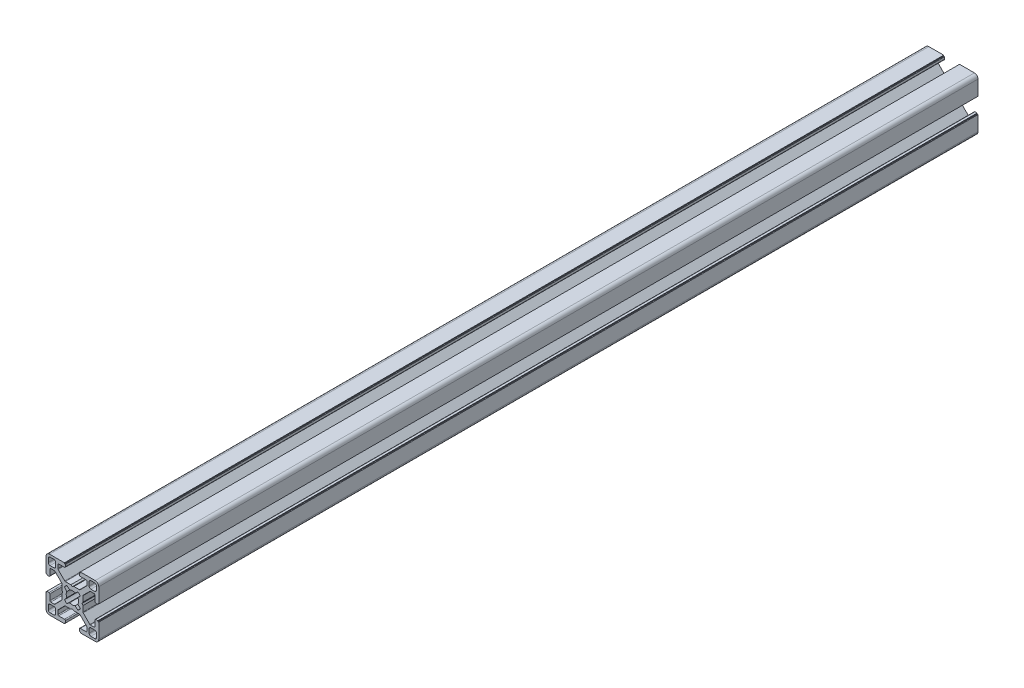
SolidWorks part; units mm, degrees
ref_plane "Front Plane" through (0, 0, 0) normal (0, 0, 1) x (1, 0, 0)
ref_plane "Top Plane" through (0, 0, 0) normal (0, 1, 0) x (1, 0, 0)
ref_plane "Right Plane" through (0, 0, 0) normal (1, 0, 0) x (0, 0, -1)
sketch "Sketch1" plane through (0, 0, 0) normal (0, 0, 1) x (1, 0, 0)
  line L0 (-15, 0) -> (15, 0) construction
  line L1 (0, -15) -> (0, 15) construction
  line L2 (-4.5, 15) -> (4.5, 15) construction
  line L3 (-4, -15) -> (4, -15) construction
  line L4 (-4.5, 15) -> (-4.5, 14.5)
  line L5 (-4.5, 14.5) -> (-4, 14.5)
  line L6 (-4, 14.5) -> (-4, 13.29)
  line L7 (-4.5, 12.79) -> (-7.7675, 12.79)
  line L8 (-8.2675, 12.29) -> (-8.2675, 10.2707)
  line L9 (-8.1211, 9.9171) -> (-4.3504, 6.1464)
  line L10 (-3.9968, 6) -> (0, 6)
  line L11 (0, 0) -> (-15, 15) construction
  line L12 (-4.5, 15) -> (-12.968, 15)
  line L14 (-12.705, 9.5135) -> (-10.5135, 9.5135)
  line L15 (-13.705, 10.5135) -> (-13.705, 12.705)
  line L16 (-12.705, 13.705) -> (-10.5135, 13.705)
  line L17 (-9.5135, 10.5135) -> (-9.5135, 12.705)
  line L18 (-13.705, 9.5135) -> (-9.5135, 13.705) construction
  line L19 (-13.705, 13.705) -> (-9.5135, 9.5135) construction
  line L20 (-3.1568, 4.5038) -> (-1.5303, 3.1477) construction
  line L21 (-4.5038, 3.1568) -> (-3.1477, 1.5303) construction
  line L22 (-6, 3.9968) -> (-6, 0)
  line L23 (-9.9171, 8.1211) -> (-6.1464, 4.3504)
  line L24 (-15, 4.5) -> (-15, 12.968)
  line L25 (-12.29, 8.2675) -> (-10.2707, 8.2675)
  line L26 (-12.79, 4.5) -> (-12.79, 7.7675)
  line L27 (-14.5, 4) -> (-13.29, 4)
  line L28 (-14.5, 4.5) -> (-14.5, 4)
  line L29 (-15, 4.5) -> (-14.5, 4.5)
  circle A0 centre (0, 0) radius 3.5
  arc A1 (-12.968, 15) -> (-15, 12.968) centre (-12.968, 12.968) ccw
  circle A2 centre (0, 0) radius 5.5 construction
  arc A3 (-10.5135, 9.5135) -> (-9.5135, 10.5135) centre (-10.5135, 10.5135) ccw
  arc A4 (-13.705, 12.705) -> (-12.705, 13.705) centre (-12.705, 12.705) cw
  arc A5 (-10.5135, 13.705) -> (-9.5135, 12.705) centre (-10.5135, 12.705) cw
  arc A6 (-12.705, 9.5135) -> (-13.705, 10.5135) centre (-12.705, 10.5135) cw
  arc A7 (-12.79, 4.5) -> (-13.29, 4) centre (-13.29, 4.5) cw
  arc A8 (-12.29, 8.2675) -> (-12.79, 7.7675) centre (-12.29, 7.7675) ccw
  arc A9 (-9.9171, 8.1211) -> (-10.2707, 8.2675) centre (-10.2707, 7.7675) ccw
  arc A10 (-6, 3.9968) -> (-6.1464, 4.3504) centre (-6.5, 3.9968) ccw
  arc A11 (-4.3504, 6.1464) -> (-3.9968, 6) centre (-3.9968, 6.5) ccw
  arc A12 (-4, 13.29) -> (-4.5, 12.79) centre (-4.5, 13.29) cw
  arc A13 (-7.7675, 12.79) -> (-8.2675, 12.29) centre (-7.7675, 12.29) ccw
  arc A14 (-8.2675, 10.2707) -> (-8.1211, 9.9171) centre (-7.7675, 10.2707) ccw
  point P4 (0, 0)
  point P8 (0, 0)
  point P13 (0, 15)
  point P15 (0, -15)
  point P16 (0, 6)
  point P23 (-11.6092, 11.6093)
  point P26 (0, 6)
  point P62 (-12.79, 4)
  point P65 (-12.79, 8.2675)
  point P68 (-10.0636, 8.2675)
  point P71 (-6, 4.2039)
  point P74 (-4.2039, 6)
  point P77 (-4, 12.79)
  point P80 (-8.2675, 12.79)
  point P83 (-8.2675, 10.0636)
  dimension "Center Hole Diameter" = 7
  dimension "D11" = 2.032
  dimension "D9" = 11
  dimension "D13" = 1
  dimension "D14" = 0.5
  dimension "Rail Height" = 30
  dimension "Rail Width" = 30
  dimension "T-Slot Width" = 8
  dimension "T-Slot Depth" = 9
  dimension "D1" = 9
  dimension "D2" = 45
  dimension "D3" = 8
  dimension "D4" = 2.21
  dimension "D5" = 16.535
  dimension "D7" = 2.54
  dimension "D6" = 1.295
  dimension "D8" = 1.246
  dimension "D10" = 10.36
  dimension "D12" = 1.905
sketch "Sketch2" plane through (0, 0, 0) normal (1, 0, 0) x (0, 0, -1)
  line L0 (-76.2, 0) -> (76.2, 0) construction
  line L2 (0, -15) -> (0, 15) construction
  line L3 (0, -15) -> (0, 15) construction
  line L4 (-76.2, -15) -> (-76.2, 15) construction
  line L5 (76.2, -15) -> (76.2, 15) construction
  point P0 (-38.7, 0)
  point P3 (0, 0)
  point P4 (38.7, 0)
  point P12 (-76.2, 0)
  point P14 (76.2, 0)
  dimension "Length" = 152.4
  dimension "D1" = 37.5
sketch "Sketch3" plane through (0, 0, 0) normal (0, 0, 1) x (1, 0, 0)
  line L0 (-4.5038, 3.1568) -> (-3.1477, 1.5303)
  line L1 (0, 3.5) -> (0, 5.5)
  line L2 (-5.5, 0) -> (-3.5, 0)
  line L7 (-6, 3.9968) -> (-6, 0) construction
  line L31 (-9.9171, 8.1211) -> (-6.1464, 4.3504) construction
  line L117 (-12.29, 8.2675) -> (-10.2707, 8.2675) construction
  line L118 (-12.79, 4.5) -> (-12.79, 7.7675) construction
  line L157 (-12.705, 9.5135) -> (-10.5135, 9.5135)
  line L158 (-9.5135, 10.5135) -> (-9.5135, 12.705)
  line L163 (-10.5135, 13.705) -> (-12.705, 13.705)
  line L164 (-13.705, 12.705) -> (-13.705, 10.5135)
  line L165 (-12.705, 9.5135) -> (-10.5135, 9.5135)
  line L166 (-9.5135, 10.5135) -> (-9.5135, 12.705)
  line L167 (-10.5135, 13.705) -> (-12.705, 13.705)
  line L168 (-13.705, 12.705) -> (-13.705, 10.5135)
  line L169 (-14.5, 4) -> (-13.29, 4) construction
  line L170 (-14.5, 4.5) -> (-14.5, 4) construction
  line L171 (-15, 4.5) -> (-14.5, 4.5) construction
  line L172 (-15, 4.5) -> (-15, 12.968) construction
  line L173 (-4.5, 15) -> (-12.968, 15) construction
  line L174 (-4.5, 15) -> (-4.5, 14.5) construction
  line L175 (-4.5, 14.5) -> (-4, 14.5) construction
  line L176 (-4, 14.5) -> (-4, 13.29) construction
  line L177 (-4.5, 12.79) -> (-7.7675, 12.79) construction
  line L178 (-8.2675, 12.29) -> (-8.2675, 10.2707) construction
  line L179 (-8.1211, 9.9171) -> (-4.3504, 6.1464) construction
  line L180 (-3.9968, 6) -> (0, 6) construction
  line L181 (-6, 3.9968) -> (-6, 0.866)
  line L182 (-9.9171, 8.1211) -> (-6.1464, 4.3504)
  line L183 (-12.29, 8.2675) -> (-10.2707, 8.2675)
  line L184 (-12.79, 4.5) -> (-12.79, 7.7675)
  line L185 (-14.5, 4) -> (-13.29, 4)
  line L186 (-14.5, 4.5) -> (-14.5, 4)
  line L187 (-15, 4.5) -> (-14.5, 4.5)
  line L188 (-15, 4.5) -> (-15, 12.968)
  line L189 (-4.5, 15) -> (-12.968, 15)
  line L190 (-4.5, 15) -> (-4.5, 14.5)
  line L191 (-4.5, 14.5) -> (-4, 14.5)
  line L192 (-4, 14.5) -> (-4, 13.29)
  line L193 (-4.5, 12.79) -> (-7.7675, 12.79)
  line L194 (-8.2675, 12.29) -> (-8.2675, 10.2707)
  line L195 (-8.1211, 9.9171) -> (-4.3504, 6.1464)
  line L196 (-3.9968, 6) -> (-0.866, 6)
  line L197 (-0.866, 6) -> (0, 5.5)
  line L198 (0, -15) -> (0, 15) construction
  line L199 (0, 0) -> (-15, 15) construction
  line L200 (0, 0) -> (-15, 15) construction
  line L201 (-3.1568, 4.5038) -> (-1.5303, 3.1477) construction
  line L202 (-3.1568, 4.5038) -> (-1.5303, 3.1477)
  line L203 (-6, 0.866) -> (-5.5, 0)
  line L204 (-15, 0) -> (15, 0) construction
  line L205 (-15, 0) -> (15, 0) construction
  line L206 (0, -15) -> (0, 15) construction
  arc A0 (-3.5, 0) -> (-3.1477, 1.5303) centre (0, 0) cw
  arc A10 (-6, 3.9968) -> (-6.1464, 4.3504) centre (-6.5, 3.9968) ccw construction
  circle A16 centre (0, 0) radius 3.5
  arc A18 (0, 3.5) -> (-1.5303, 3.1477) centre (0, 0) ccw
  arc A20 (-9.9171, 8.1211) -> (-10.2707, 8.2675) centre (-10.2707, 7.7675) ccw construction
  arc A22 (-12.29, 8.2675) -> (-12.79, 7.7675) centre (-12.29, 7.7675) ccw construction
  arc A28 (-13.29, 4) -> (-12.79, 4.5) centre (-13.29, 4.5) ccw construction
  arc A29 (-10.5135, 9.5135) -> (-9.5135, 10.5135) centre (-10.5135, 10.5135) ccw
  arc A30 (-9.5135, 12.705) -> (-10.5135, 13.705) centre (-10.5135, 12.705) ccw
  arc A31 (-12.705, 13.705) -> (-13.705, 12.705) centre (-12.705, 12.705) ccw
  arc A32 (-13.705, 10.5135) -> (-12.705, 9.5135) centre (-12.705, 10.5135) ccw
  arc A33 (-10.5135, 9.5135) -> (-9.5135, 10.5135) centre (-10.5135, 10.5135) ccw
  arc A34 (-9.5135, 12.705) -> (-10.5135, 13.705) centre (-10.5135, 12.705) ccw
  arc A35 (-12.705, 13.705) -> (-13.705, 12.705) centre (-12.705, 12.705) ccw
  arc A36 (-13.705, 10.5135) -> (-12.705, 9.5135) centre (-12.705, 10.5135) ccw
  arc A37 (-12.968, 15) -> (-15, 12.968) centre (-12.968, 12.968) ccw construction
  arc A38 (-4.5, 12.79) -> (-4, 13.29) centre (-4.5, 13.29) ccw construction
  arc A39 (-7.7675, 12.79) -> (-8.2675, 12.29) centre (-7.7675, 12.29) ccw construction
  arc A40 (-8.2675, 10.2707) -> (-8.1211, 9.9171) centre (-7.7675, 10.2707) ccw construction
  arc A41 (-4.3504, 6.1464) -> (-3.9968, 6) centre (-3.9968, 6.5) ccw construction
  arc A42 (-6, 3.9968) -> (-6.1464, 4.3504) centre (-6.5, 3.9968) ccw
  arc A43 (-9.9171, 8.1211) -> (-10.2707, 8.2675) centre (-10.2707, 7.7675) ccw
  arc A44 (-12.29, 8.2675) -> (-12.79, 7.7675) centre (-12.29, 7.7675) ccw
  arc A45 (-13.29, 4) -> (-12.79, 4.5) centre (-13.29, 4.5) ccw
  arc A46 (-12.968, 15) -> (-15, 12.968) centre (-12.968, 12.968) ccw
  arc A47 (-4.5, 12.79) -> (-4, 13.29) centre (-4.5, 13.29) ccw
  arc A48 (-7.7675, 12.79) -> (-8.2675, 12.29) centre (-7.7675, 12.29) ccw
  arc A49 (-8.2675, 10.2707) -> (-8.1211, 9.9171) centre (-7.7675, 10.2707) ccw
  arc A50 (-4.3504, 6.1464) -> (-3.9968, 6) centre (-3.9968, 6.5) ccw
  circle A51 centre (0, 0) radius 5.5 construction
  arc A52 (-3.1568, 4.5038) -> (-4.5038, 3.1568) centre (0, 0) ccw
  dimension "D3" = 60
  dimension "D4" = 60
  dimension "D1" = 0
  dimension "D2" = 0
extrude "Boss-Extrude1" add sketch "Sketch3" along normal mid plane 500
pattern_circular "CirPattern1" count 4 over 360 about axis through (0, 0, 0) along (0, 0, 1) of "Boss-Extrude1"
ref_plane "Contact Plane1" through (15, 0, 0) normal (1, 0, 0) x (0, 0, -1)
ref_plane "Contact Plane2" through (0, -15, 0) normal (0, 1, 0) x (1, 0, 0)
ref_plane "Contact Plane3" through (-15, 0, 0) normal (1, 0, 0) x (0, 0, -1)
ref_plane "Contact Plane4" through (0, 15, 0) normal (0, 1, 0) x (1, 0, 0)
equation "\"D1@Sketch2\" = \"Rail Height@Sketch1\" * 1.25"
equation "\"D1@Sketch1\"=\"T-Slot Width@Sketch1\"+1mm"
equation "\"D3@Sketch1\"=\"T-Slot Width@Sketch1\""
equation "\"D1@Boss-Extrude1\"=\"Width\""
equation "\"Width\" = 500mm"
